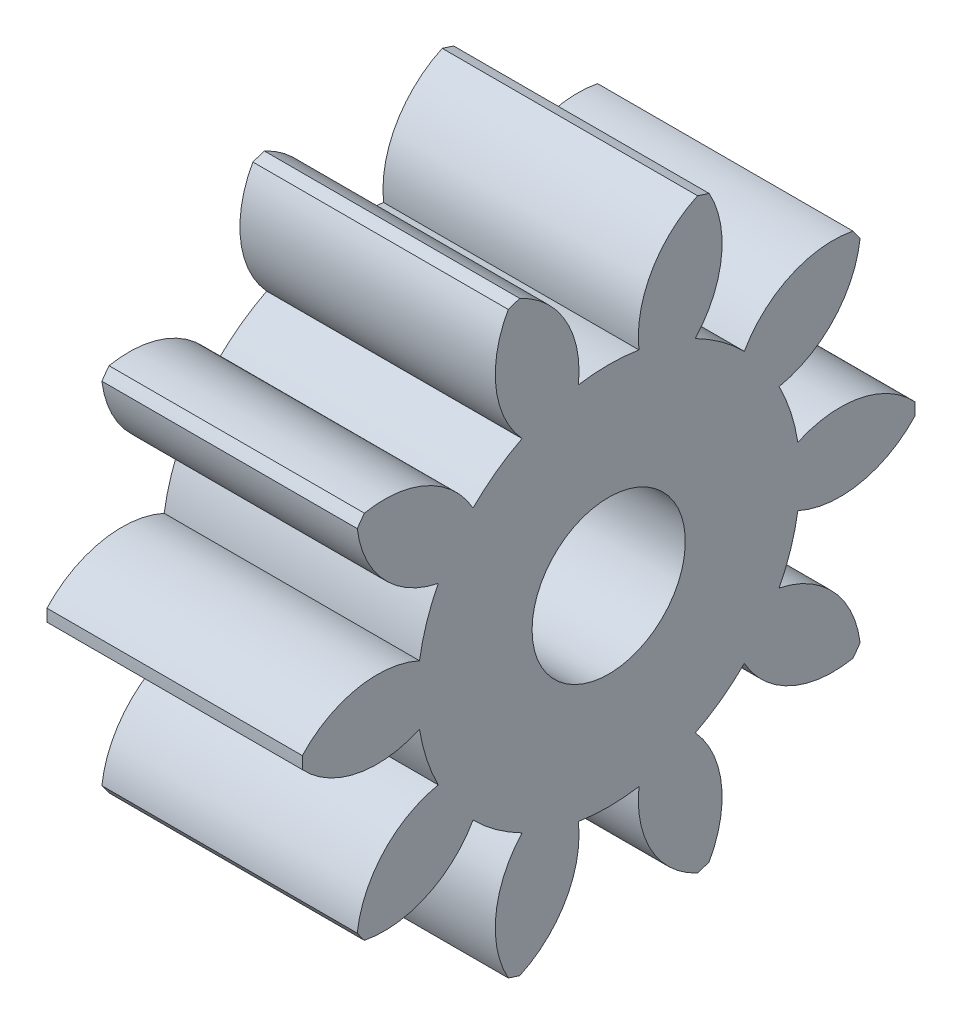
SolidWorks part; units mm, degrees
ref_plane "Plane1" through (0, 0, 0) normal (0, 0, 1) x (1, 0, 0)
ref_plane "Plane2" through (0, 0, 0) normal (0, 1, 0) x (1, 0, 0)
ref_plane "Plane3" through (0, 0, 0) normal (1, 0, 0) x (0, 0, -1)
sketch "HoldingSke" plane through (0, 0, 0) normal (0, 1, 0) x (1, 0, 0)
  line L0 (0, 0) -> (0.9848, -0.1736)
  line L1 (-15, 0) -> (100, 0) construction
  line L2 (0, 0) -> (-2.1039, 2.3779)
  line L3 (0, 0) -> (-11.863, 4.5341)
  line L4 (0, 0) -> (8.5048, 1.4996)
  line L5 (0, 0) -> (-46.8476, -17.4728)
  line L6 (0, 0) -> (-4.1448, -2.7965)
  line L7 (-2.1039, 2.3779) -> (8.6586, 51.2059)
  line L8 (-76.2, 54.61) -> (-75.7, 54.61)
  line L9 (-71.009, 38.7566) -> (-53.1078, 45.2721)
  line L10 (-76.2, 71.12) -> (104.1128, 71.12)
  line L11 (0, 0) -> (-5, 0)
  line L12 (-76.2, 101.6) -> (-76.162, 101.6)
  line L13 (24.9733, 27.94) -> (52.9518, 28.4284)
  line L14 (24.9733, 27.94) -> (24.9743, 27.94)
  line L15 (24.9733, 27.94) -> (100.4006, 29.5858)
  line L16 (-63.627, -1) -> (-12.827, -1)
  circle A0 centre (0, 0) radius 1.5
  circle A1 centre (0, 0) radius 3.749
  circle A2 centre (0, 0) radius 37.5
  circle A3 centre (0, 0) radius 1.5
  dimension "MHD" = 7.498
  dimension "Hub_dia" = 75
  dimension "Bore" = 3
  dimension "MBD" = 3
  dimension "Num_teeth" = 10
  dimension "Pitch" = 1
  dimension "Overall_len" = 50
  dimension "Show_teeth" = 10
  dimension "Thickness" = 5
  dimension "OAL" = 50.0001
  dimension "T_dim" = 0.5
  dimension "Ap" = 20
  dimension "H" = 19.05
  dimension "Pitch_radius" = 180.3128
  dimension "Width" = 5
  dimension "Backlash" = 0.038
  dimension "Addendum_fac" = 1
  dimension "Dedendum_fac" = 1.25
  dimension "Clearance_fac" = 0.25
  dimension "Dedendum_add" = 0.001
  dimension "Module" = 1
sketch "BasProSke" plane through (0, 0, 0) normal (0, 1, 0) x (1, 0, 0)
  line L0 (-10, 0) -> (60, 0) construction
  line L1 (0, 0) -> (0, 6)
  line L2 (0, 0) -> (5, 0)
  line L3 (5, 0) -> (5, 6)
  line L4 (5, 6) -> (0, 6)
  dimension "Thickness" = 5
  dimension "Diameter" = 12
revolve "Base-Revolve" add sketch "BasProSke" angle 360 about L0
sketch "TooCutSke" plane through (0, 0, 0) normal (1, 0, 0) x (0, 0, -1)
  line L1 (0, 0) -> (0, 107) construction
  line L2 (0, 0) -> (-0.8485, 4.9275) construction
  line L3 (0, 0) -> (-3.0584, 9.4126) construction
  line L4 (-0.8485, 4.9275) -> (-1.5292, 4.7063) construction
  arc A0 (0.5928, 3.7018) -> (-0.5928, 3.7018) centre (0, 0) ccw
  arc A1 (1.7758, 5.7578) -> (-1.7758, 5.7578) centre (0, 0) ccw
  circle A2 centre (0, 0) radius 5 construction
  circle A3 centre (0, 0) radius 4.6985 construction
  arc A4 (-0.5928, 3.7018) -> (-1.7758, 5.7578) centre (-2.5801, 3.9267) ccw
  arc A5 (1.7758, 5.7578) -> (0.5928, 3.7018) centre (2.5801, 3.9267) ccw
  dimension "Root_dia" = 7.498
  dimension "Overcut_dia" = 12.0508
  dimension "Pitch_dia" = 10
  dimension "Base_dia" = 9.3969
  dimension "Flank_rad" = 2
  dimension "Half_ang" = 18
  dimension "Half_CT" = 0.7157
extrude "ToothCut" cut sketch "TooCutSke" along normal through all
fillet "Breaks" [suppressed] radius 0.02
fillet "RootFillets" [suppressed] radius 0.251
pattern_circular "TeethCuts" count 10 every 36 about axis through (-10, 0, 0) along (1, 0, 0) of "ToothCut", "RootFillets", "Breaks"
sketch "HubNeaOneSke" plane through (0, 0, 0) normal (-1, 0, 0) x (0, 0, 1)
  circle A0 centre (0, 0) radius 3.749
  dimension "Diameter" = 7.498
extrude "HubNearOne" [suppressed] add sketch "HubNeaOneSke" along normal blind 45.0001
sketch "HubNeaBotSke" plane through (0, 0, 0) normal (-1, 0, 0) x (0, 0, 1)
  circle A0 centre (0, 0) radius 3.749
  dimension "Diameter" = 7.498
extrude "HubNearBoth" [suppressed] add sketch "HubNeaBotSke" along normal blind 22.5
ref_plane "FarPln" through (5, 0, 0) normal (1, 0, 0) x (0, 0, -1)
sketch "HubFarSke" plane through (5, 0, 0) normal (1, 0, 0) x (0, 0, -1)
  circle A0 centre (0, 0) radius 3.749
  dimension "Diameter" = 7.498
extrude "HubFar" [suppressed] add sketch "HubFarSke" along normal blind 22.5
sketch "BorSke" plane through (0, 0, 0) normal (1, 0, 0) x (0, 0, -1)
  circle A0 centre (0, 0) radius 1.5
  dimension "Diameter" = 3
extrude "Bore" cut sketch "BorSke" along normal mid plane 100.0001
sketch "KeySke" plane through (0, 0, 0) normal (1, 0, 0) x (0, 0, -1)
  line L0 (-0.6, 0) -> (-0.6, 2)
  line L1 (-0.6, 2) -> (0.6, 2)
  line L2 (0.6, 2) -> (0.6, 0)
  line L3 (0, 0) -> (0, 34) construction
  line L4 (-0.6, 0) -> (0.6, 0)
  dimension "Offset" = 2
  dimension "Width" = 1.2
extrude "Keyway" [suppressed] cut sketch "KeySke" along normal mid plane 100.0001
pattern_circular "Keyway2" [suppressed] count 2 every 90 about axis through (-10, 0, 0) along (1, 0, 0)
equation "' \"Module@HoldingSke\" = 6.35"
equation "' \"Num_teeth@HoldingSke\" = 12"
equation "' \"Ap@HoldingSke\" =  20"
equation "' \"Ap@HoldingSke\" = 20"
equation "' \"Width@HoldingSke\" = 0.5 * 25.4"
equation "' \"Hub_dia@HoldingSke\"= 1 * 25.4"
equation "' \"Hub_dia@HoldingSke\" = 1 * 25.4"
equation "' \"Overall_len@HoldingSke\" = 1.0 * 25.4"
equation "' \"Bore@HoldingSke\" = 0.75 * 25.4"
equation "' \"T_dim@HoldingSke\" = 0.1 * 25.4"
equation "' \"Width@KeySke\" = 0.25 * 25.4"
equation "' \"Show_teeth@HoldingSke\" = 13"
equation "' \"Backlash@HoldingSke\" = 0.009 * 25.4"
equation "' \"Addendum_fac@HoldingSke\" = 1.0"
equation "' \"Dedendum_fac@HoldingSke\" = 1.25"
equation "' \"Dedendum_add@HoldingSke\" = 0.00005 * 25.4"
equation "' \"Clearance_fac@HoldingSke\" = 0.25"
equation "\"Pitch@HoldingSke\" = 1 / \"Module@HoldingSke\""
equation "\"Overcut_dia@TooCutSke\" = (\"Num_teeth@HoldingSke\" + 2 * \"Addendum_fac@HoldingSke\") / \"Pitch@HoldingSke\" + 0.002 * 25.4"
equation "\"Pitch_dia@TooCutSke\" = \"Num_teeth@HoldingSke\" / \"Pitch@HoldingSke\""
equation "\"Base_dia@TooCutSke\" = \"Num_teeth@HoldingSke\" / \"Pitch@HoldingSke\" * cos((\"Ap@HoldingSke\"  * 3.14159265 / 180))"
equation "\"Root_dia@TooCutSke\" = (\"Num_teeth@HoldingSke\" + 2) / \"Pitch@HoldingSke\" - 2 * (\"Addendum_fac@HoldingSke\" + \"Dedendum_fac@HoldingSke\") / \"Pitch@HoldingSke\" - \"Dedendum_add@HoldingSke\" * 2"
equation "\"Half_ang@TooCutSke\" = 180 / \"Num_teeth@HoldingSke\""
equation "\"Half_CT@TooCutSke\" = \"Num_teeth@HoldingSke\" / \"Pitch@HoldingSke\" * sin((3.14159265 / 2 / \"Num_teeth@HoldingSke\")) / 2 - 7 * \"Backlash@HoldingSke\" / 4"
equation "\"Flank_rad@TooCutSke\" = \"Num_teeth@HoldingSke\" / \"Pitch@HoldingSke\" / 5"
equation "\"Radius@RootFillets\" = \"Clearance_fac@HoldingSke\" / \"Pitch@HoldingSke\" + \"Dedendum_add@HoldingSke\""
equation "\"Break_rad@Breaks\" = 0.02 / \"Pitch@HoldingSke\""
equation "\"Thickness@HoldingSke\" = \"Width@HoldingSke\""
equation "\"OAL@HoldingSke\" = \"Thickness@HoldingSke\""
equation "\"MHD@HoldingSke\" = (\"Num_teeth@HoldingSke\" + 2) / \"Pitch@HoldingSke\" - 2 * (\"Addendum_fac@HoldingSke\" + \"Dedendum_fac@HoldingSke\")  / \"Pitch@HoldingSke\" - \"Dedendum_add@HoldingSke\" * 2"
equation "\"MBD@HoldingSke\" = (\"Num_teeth@HoldingSke\" + 2) / \"Pitch@HoldingSke\" - 2 * (\"Addendum_fac@HoldingSke\" + \"Dedendum_fac@HoldingSke\")  / \"Pitch@HoldingSke\" - \"Dedendum_add@HoldingSke\" * 2 - 0.002 * 25.4"
equation "\"MHD@HoldingSke\" = ((sgn( \"MHD@HoldingSke\" - \"Hub_dia@HoldingSke\" )-1)*( \"MHD@HoldingSke\" - \"Hub_dia@HoldingSke\" ))/-2+ \"Hub_dia@HoldingSke\""
equation "\"MBD@HoldingSke\" = ((sgn( \"MBD@HoldingSke\" - \"Bore@HoldingSke\" )-1)*( \"MBD@HoldingSke\" - \"Bore@HoldingSke\" ))/-2+ \"Bore@HoldingSke\""
equation "\"OAL@HoldingSke\" = ((sgn( \"OAL@HoldingSke\" - \"Overall_len@HoldingSke\" )+1)*( \"OAL@HoldingSke\" - \"Overall_len@HoldingSke\" ))/2 + \"Overall_len@HoldingSke\" + 0.000002 * 25.4"
equation "\"Num_teeth@TeethCuts\" = int( \"Show_teeth@HoldingSke\" ) + 1"
equation "\"Num_teeth@TeethCuts\" = ((sgn( \"Num_teeth@TeethCuts\" - \"Num_teeth@HoldingSke\" )-1)*( \"Num_teeth@TeethCuts\" - \"Num_teeth@HoldingSke\" ))/-2+ \"Num_teeth@HoldingSke\""
equation "\"Num_teeth@TeethCuts\" = ((sgn( \"Num_teeth@TeethCuts\" - 2.0)+1)*( \"Num_teeth@TeethCuts\" - 2.0))/2 +2.0"
equation "\"Angle@TeethCuts\" = 360.0 / \"Num_teeth@HoldingSke\""
equation "\"Diameter@BasProSke\" = (\"Num_teeth@HoldingSke\" + 2 * \"Addendum_fac@HoldingSke\") / \"Pitch@HoldingSke\""
equation "\"Thickness@BasProSke\"  = \"Thickness@HoldingSke\""
equation "' \"Fillet_rad@BasProSke\" =  \"Thickness@HoldingSke\" * 0.05"
equation "' \"Fillet_rad@BasProSke\" = \"Thickness@HoldingSke\" * 0.05"
equation "\"MHD@HoldingSke\" = ((sgn( \"MHD@HoldingSke\" - \"Root_dia@TooCutSke\" )-1)*( \"MHD@HoldingSke\" - \"Root_dia@TooCutSke\" ))/-2+ \"Root_dia@TooCutSke\""
equation "\"Diameter@HubNeaOneSke\" = \"MHD@HoldingSke\""
equation "\"Length@HubNearOne\" = \"OAL@HoldingSke\" - \"Thickness@BasProSke\""
equation "\"Diameter@HubNeaBotSke\" = \"MHD@HoldingSke\""
equation "\"Length@HubNearBoth\" = ( \"OAL@HoldingSke\" - \"Thickness@BasProSke\" ) / 2.0"
equation "\"Thickness@FarPln\" = \"Thickness@BasProSke\""
equation "\"Diameter@HubFarSke\" = \"MHD@HoldingSke\""
equation "\"Length@HubFar\" = ( \"OAL@HoldingSke\" - \"Thickness@BasProSke\" ) / 2.0"
equation "\"Diameter@BorSke\" = \"MBD@HoldingSke\""
equation "\"D1@Bore\" = \"OAL@HoldingSke\" * 2.0"
equation "\"D1@Keyway\" = \"OAL@HoldingSke\" * 2.0"
equation "\"Offset@KeySke\" = \"T_dim@HoldingSke\" + \"MBD@HoldingSke\" / 2.0"
